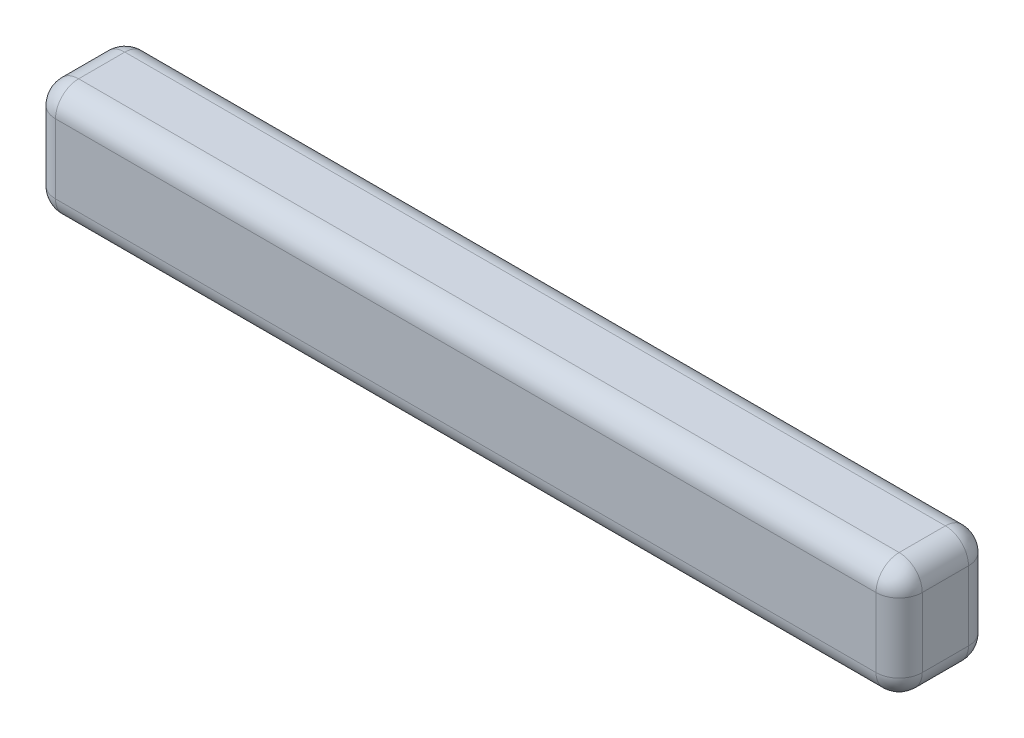
SolidWorks part; units mm, degrees
ref_plane "Front Plane" through (0, 0, 0) normal (0, 0, 1) x (1, 0, 0)
ref_plane "Top Plane" through (0, 0, 0) normal (0, 1, 0) x (1, 0, 0)
ref_plane "Right Plane" through (0, 0, 0) normal (1, 0, 0) x (0, 0, -1)
sketch "Sketch1" plane through (0, 0, 0) normal (0, 1, 0) x (1, 0, 0)
  line L1 (-18.75, -2) -> (18.75, -2)
  line L2 (-18.75, -2) -> (-18.75, 2)
  line L3 (-18.75, 2) -> (18.75, 2)
  line L4 (18.75, -2) -> (18.75, 2)
  line L5 (-18.75, -2) -> (18.75, 2) construction
  line L6 (-18.75, 2) -> (18.75, -2) construction
  point P0 (0, 0)
  dimension "D1" = 4
  dimension "D2" = 37.5
extrude "Boss-Extrude1" add sketch "Sketch1" along normal blind 5
fillet "Fillet1" radius 1 12 edges at (-18.75, 2.5, -2) (-18.75, 5, 0) (-18.75, 2.5, 2) (-18.75, 0, 0) (18.75, 2.5, 2) (18.75, 5, 0) (18.75, 2.5, -2) (18.75, 0, 0) (0, 0, 2) (0, 0, -2) (0, 5, -2) (0, 5, 2)
